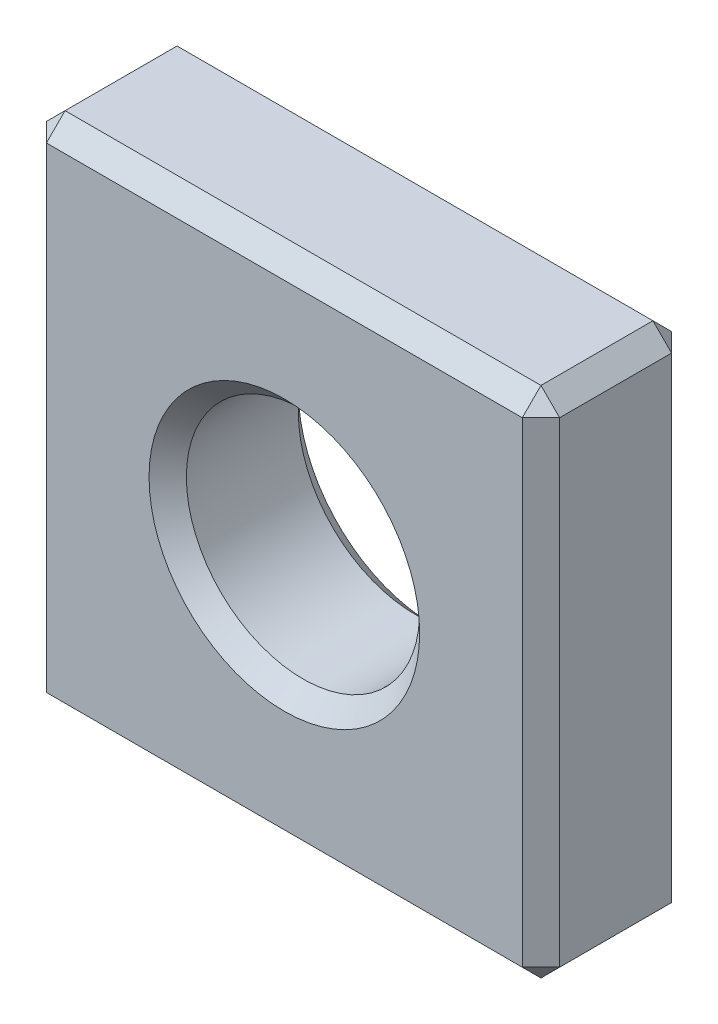
SolidWorks part; units mm, degrees
material "Plain Carbon Steel"
ref_plane "Front Plane" through (0, 0, 0) normal (0, 0, 1) x (1, 0, 0)
ref_plane "Top Plane" through (0, 0, 0) normal (0, 1, 0) x (1, 0, 0)
ref_plane "Right Plane" through (0, 0, 0) normal (1, 0, 0) x (0, 0, -1)
sketch "Sketch1" plane through (0, 0, 0) normal (0, 0, 1) x (1, 0, 0)
  line L1 (-2.75, -2.75) -> (2.75, -2.75)
  line L2 (-2.75, -2.75) -> (-2.75, 2.75)
  line L3 (-2.75, 2.75) -> (2.75, 2.75)
  line L4 (2.75, -2.75) -> (2.75, 2.75)
  line L5 (-2.75, -2.75) -> (2.75, 2.75) construction
  line L6 (-2.75, 2.75) -> (2.75, -2.75) construction
  circle A0 centre (0, 0) radius 1.25
  point P0 (0, 0)
  dimension "D2" = 2.5
  dimension "D1" = 5.5
extrude "Boss-Extrude1" add sketch "Sketch1" along normal blind 1.6
chamfer "Chamfer1" distance 0.2 angle 45 14 edges at (1.25, 0, 0) (1.25, 0, 1.6) (2.75, -2.75, 0.8) (-2.75, -2.75, 0.8) (2.75, 2.75, 0.8) (0, 2.75, 0) (2.75, 0, 0) (0, -2.75, 0) (-2.75, 0, 0) (-2.75, 2.75, 0.8) (0, -2.75, 1.6) (-2.75, 0, 1.6) (0, 2.75, 1.6) (2.75, 0, 1.6)
